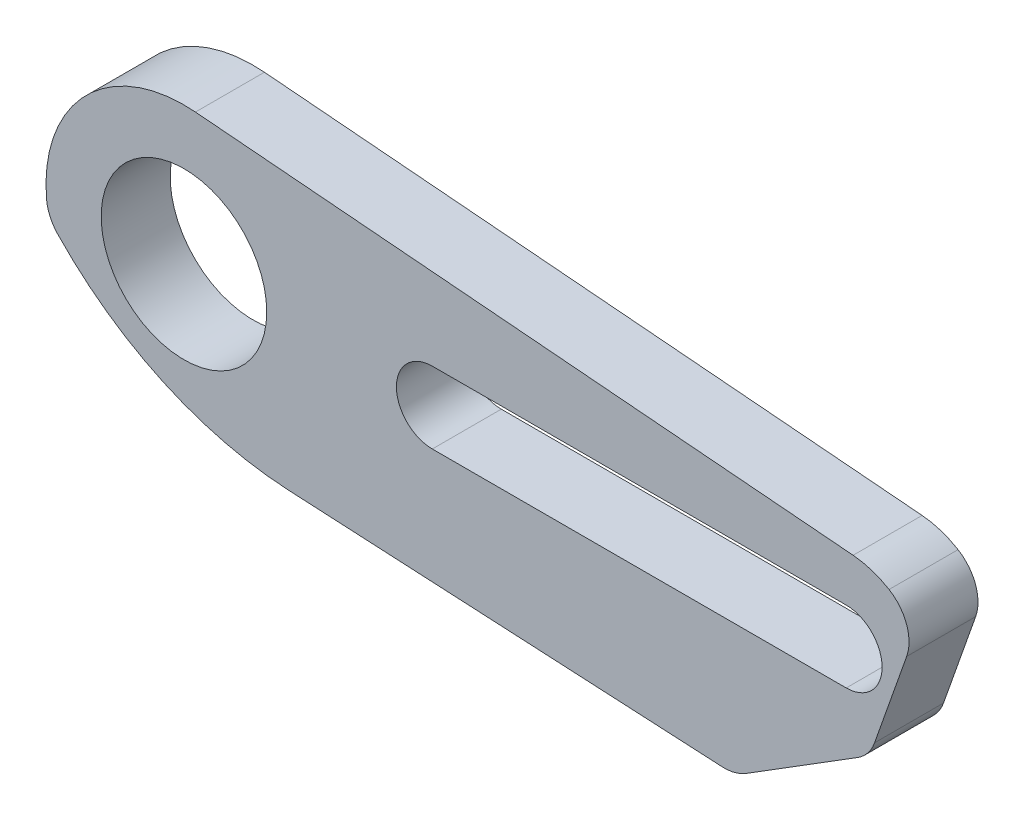
SolidWorks part; units mm, degrees
material "Thornel Mat VMA"
ref_plane "前视基准面" through (0, 0, 0) normal (0, 0, 1) x (1, 0, 0)
ref_plane "上视基准面" through (0, 0, 0) normal (0, 1, 0) x (1, 0, 0)
ref_plane "右视基准面" through (0, 0, 0) normal (1, 0, 0) x (0, 0, -1)
other "Configuration Table"
sketch "草图1" plane through (0, 0, 0) normal (0, 0, 1) x (1, 0, 0)
  line L0 (0, -5) -> (19.9726, -6.0467)
  line L3 (9, 0) -> (24, 0) construction
  line L4 (9, 1.3) -> (24, 1.3)
  line L5 (9, -1.3) -> (24, -1.3)
  line L6 (19.9726, -6.0467) -> (25.5873, -2.5457)
  line L7 (0, 5.0175) -> (24.25, 2.9896)
  circle A0 centre (0, 0) radius 3
  arc A3 (9, 1.3) -> (9, -1.3) centre (9, 0) ccw
  arc A4 (24, -1.3) -> (24, 1.3) centre (24, 0) ccw
  arc A5 (0.4167, 4.9826) -> (0, -5) centre (0, 0) ccw
  arc A6 (25.5873, -2.5457) -> (24.25, 2.9896) centre (24, 0) ccw
  point P11 (16.5, 0)
  dimension "D2" = 6
  dimension "D3" = 15
  dimension "D4" = 1.3
  dimension "D5" = 10
  dimension "D7" = 6
  dimension "D1" = 24
  dimension "D6" = 3
  dimension "D8" = 20
extrude "凸台-拉伸1" add sketch "草图1" along normal blind 2.5 contours L6 A6 L7 A5 L0 A0 A4 L5 A3 L4
sketch "草图2" plane through (0, 0, 2.5) normal (0, 0, 1) x (1, 0, 0)
  line L0 (25, 2.8284) -> (22.3965, -4.5353) construction
  line L5 (19.9726, -6.0467) -> (25.5873, -2.5457) construction
  line L6 (24.8514, -3.0045) -> (25.5873, -2.5457)
  line L7 (24.8514, -3.0045) -> (26.5, 1.6583)
  arc A0 (25.5873, -2.5457) -> (24.25, 2.9896) centre (24, 0) ccw construction
  arc A1 (25.5873, -2.5457) -> (26.5, 1.6583) centre (24, 0) ccw
  dimension "D1" = 1
  dimension "D2" = 2.5
extrude "切除-拉伸2" cut sketch "草图2" against normal blind 2.5
sketch "草图3" plane through (0, 0, 2.5) normal (0, 0, 1) x (1, 0, 0)
  line L0 (0, -5) -> (19.9726, -6.0467) construction
  line L2 (0, -5) -> (19.9726, -6.0467)
  circle A0 centre (4.4685, 7.283) radius 12.5
  arc A1 (0.4167, 4.9826) -> (0, -5) centre (0, 0) ccw construction
  arc A2 (0.4167, 4.9826) -> (0, -5) centre (0, 0) ccw
  dimension "D1" = 25
  dimension "D2" = 8.5445
extrude "切除-拉伸3" cut sketch "草图3" against normal blind 20
fillet "圆角2" radius 1.5 4 edges at (19.9726, -6.0467, 1.25) (24.8514, -3.0045, 1.25) (-4.9007, -0.9916, 1.25) (26.5, 1.6583, 1.25)
